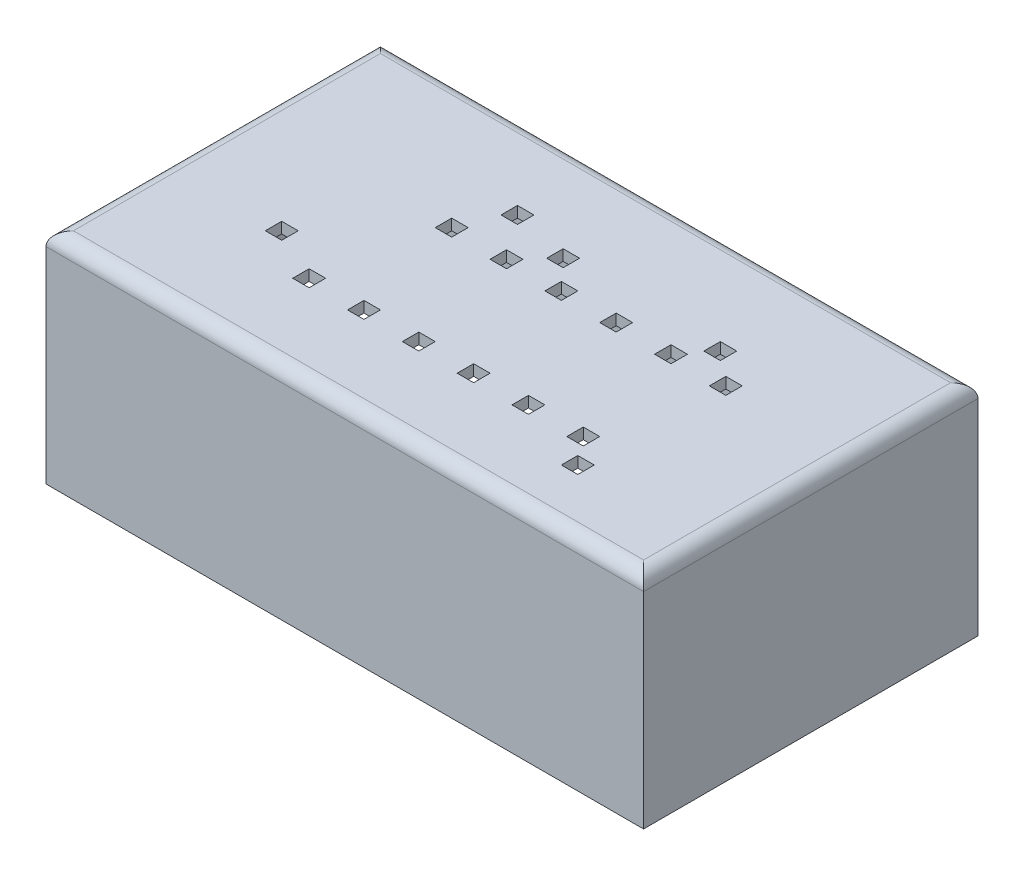
SolidWorks part; units mm, degrees
ref_plane "Front Plane" through (0, 0, 0) normal (0, 0, 1) x (1, 0, 0)
ref_plane "Top Plane" through (0, 0, 0) normal (0, 1, 0) x (1, 0, 0)
ref_plane "Right Plane" through (0, 0, 0) normal (1, 0, 0) x (0, 0, -1)
sketch "Sketch1" plane through (0, 0, 0) normal (0, 1, 0) x (1, 0, 0)
  line L1 (52.5, -28.5) -> (-52.5, -28.5)
  line L2 (52.5, -28.5) -> (52.5, 28.5)
  line L3 (52.5, 28.5) -> (-52.5, 28.5)
  line L4 (-52.5, -28.5) -> (-52.5, 28.5)
  line L5 (52.5, -28.5) -> (-52.5, 28.5) construction
  line L6 (52.5, 28.5) -> (-52.5, -28.5) construction
  point P0 (0, 0)
  dimension "D1" = 57
  dimension "D2" = 105
extrude "Boss-Extrude1" add sketch "Sketch1" against normal blind 2
sketch "Sketch2" plane through (0, 0, 0) normal (0, 1, 0) x (1, 0, 0)
  line L0 (-52.5, 28.5) -> (52.5, 28.5)
  line L1 (52.5, 28.5) -> (52.5, -28.5)
  line L2 (52.5, -28.5) -> (-52.5, -28.5)
  line L3 (-52.5, -28.5) -> (-52.5, 28.5)
  line L4 (-54.5, 30.5) -> (54.5, 30.5)
  line L5 (54.5, 30.5) -> (54.5, -30.5)
  line L6 (54.5, -30.5) -> (-54.5, -30.5)
  line L7 (-54.5, -30.5) -> (-54.5, 30.5)
  dimension "D1" = 2
  dimension "D2" = 2
  dimension "D3" = 2
  dimension "D4" = 2
extrude "Boss-Extrude2" add sketch "Sketch2" against normal blind 40
sketch "Sketch3" plane through (-54.5, 0, 0) normal (-1, 0, 0) x (0, 0, 1)
  line L0 (-21.5, -40) -> (-21.5, -26)
  line L1 (-30.5, -40) -> (30.5, -40) construction
  line L2 (-21.5, -26) -> (-8.5, -26)
  line L3 (-8.5, -26) -> (-8.5, -40)
  line L4 (-8.5, -40) -> (-21.5, -40)
  line L5 (13.5, -40) -> (13.5, -26)
  line L6 (13.5, -26) -> (23.5, -26)
  line L7 (23.5, -26) -> (23.5, -40)
  line L8 (23.5, -40) -> (13.5, -40)
  line L9 (-30.5, -40) -> (-30.5, 0) construction
  line L11 (30.5, -40) -> (30.5, 0) construction
  dimension "D1" = 9
  dimension "D2" = 14
  dimension "D3" = 13
  dimension "D4" = 7
  dimension "D5" = 10
  dimension "D6" = 14
extrude "Cut-Extrude1" cut sketch "Sketch3" against normal up to surface (2 mm away) up to face at (-52.5, -21, 0)
sketch "Sketch4" plane through (0, 0, 0) normal (0, 1, 0) x (1, 0, 0)
  line L0 (-54.5, -15.5) -> (54.5, -15.5) construction
  line L1 (-54.5, 30.5) -> (-54.5, -30.5) construction
  line L2 (54.5, -30.5) -> (54.5, 30.5) construction
  line L3 (-54.5, 5.5) -> (54.5, 5.5) construction
  line L4 (-24.5, 30.5) -> (-24.5, -30.5) construction
  line L5 (54.5, 30.5) -> (-54.5, 30.5) construction
  line L6 (-54.5, -30.5) -> (54.5, -30.5) construction
  line L7 (35.7443, 30.5) -> (35.7443, -30.5) construction
  line L9 (-21.5, -15.5) -> (-24.5, -15.5)
  line L10 (-21.5, -15.5) -> (-21.5, -12.5)
  line L11 (-21.5, -12.5) -> (-24.5, -12.5)
  line L12 (-24.5, -15.5) -> (-24.5, -12.5)
  dimension "D1" = 15
  dimension "D2" = 25
  dimension "D3" = 30
  dimension "D4" = 3
  dimension "D5" = 3
extrude "Cut-Extrude2" cut sketch "Sketch4" against normal up to surface (2 mm away) up to face at (0, -2, 0)
pattern_linear "LPattern1" count 6 spacing 10 along (1, 0, 0) of "Cut-Extrude2"
sketch "Sketch5" plane through (0, 0, 0) normal (0, 1, 0) x (1, 0, 0)
  line L0 (-54.5, 5.5) -> (54.5, 5.5) construction
  line L1 (-54.5, 30.5) -> (-54.5, -30.5) construction
  line L2 (54.5, -30.5) -> (54.5, 30.5) construction
  line L3 (-19.5, 30.5) -> (-19.5, -30.5) construction
  line L4 (54.5, 30.5) -> (-54.5, 30.5) construction
  line L5 (-54.5, -30.5) -> (54.5, -30.5) construction
  line L7 (-19.5, 5.5) -> (-16.5, 5.5)
  line L8 (-19.5, 5.5) -> (-19.5, 8.5)
  line L9 (-19.5, 8.5) -> (-16.5, 8.5)
  line L10 (-16.5, 5.5) -> (-16.5, 8.5)
  dimension "D1" = 35
  dimension "D2" = 25
  dimension "D3" = 3
  dimension "D4" = 3
extrude "Cut-Extrude3" cut sketch "Sketch5" against normal up to surface (2 mm away) up to face at (27, -2, 14)
pattern_linear "LPattern2" count 6 spacing 10 along (1, 0, 0) of "Cut-Extrude3"
sketch "Sketch6" plane through (0, 0, 0) normal (0, 1, 0) x (1, 0, 0)
  line L0 (-19.5, 8.5) -> (-19.5, 5.5) construction
  line L1 (-15.5, 16.5) -> (-12.5, 16.5)
  line L2 (-15.5, 16.5) -> (-15.5, 13.5)
  line L3 (-15.5, 13.5) -> (-12.5, 13.5)
  line L4 (-12.5, 16.5) -> (-12.5, 13.5)
  line L5 (-16.5, 5.5) -> (-19.5, 5.5) construction
  line L6 (-4.5, 13.8318) -> (-1.5, 13.8318)
  line L7 (-4.5, 13.8318) -> (-4.5, 10.8318)
  line L8 (-4.5, 10.8318) -> (-1.5, 10.8318)
  line L9 (-1.5, 13.8318) -> (-1.5, 10.8318)
  point P6 (-18, 5.5)
  dimension "D1" = 3
  dimension "D2" = 3
  dimension "D3" = 4
  dimension "D4" = 8
  dimension "D5" = 3
  dimension "D6" = 3
  dimension "D7" = 8
extrude "Cut-Extrude4" cut sketch "Sketch6" against normal up to surface (2 mm away) up to face at (32, -2, -7)
sketch "Sketch7" plane through (0, 0, 0) normal (0, 1, 0) x (1, 0, 0)
  line L0 (-54.5, 30.5) -> (-54.5, -30.5) construction
  line L1 (-34.5, -7.5) -> (-31.5, -7.5)
  line L2 (-34.5, -7.5) -> (-34.5, -10.5)
  line L3 (-34.5, -10.5) -> (-31.5, -10.5)
  line L4 (-31.5, -7.5) -> (-31.5, -10.5)
  line L5 (-54.5, -30.5) -> (54.5, -30.5) construction
  line L6 (24.5, 13.5) -> (27.5, 13.5)
  line L7 (24.5, 13.5) -> (24.5, 10.5)
  line L8 (24.5, 10.5) -> (27.5, 10.5)
  line L9 (27.5, 13.5) -> (27.5, 10.5)
  line L10 (29.5, -17.5) -> (32.5, -17.5)
  line L11 (29.5, -17.5) -> (29.5, -20.5)
  line L12 (29.5, -20.5) -> (32.5, -20.5)
  line L13 (32.5, -17.5) -> (32.5, -20.5)
  line L14 (23.5, 5.5) -> (23.5, 8.5) construction
  line L15 (28.5, -15.5) -> (28.5, -12.5) construction
  line L16 (25.5, -15.5) -> (28.5, -15.5) construction
  line L17 (23.5, 8.5) -> (20.5, 8.5) construction
  point P16 (23.5, 7)
  dimension "D1" = 3
  dimension "D2" = 20
  dimension "D3" = 20
  dimension "D4" = 3
  dimension "D5" = 3
  dimension "D6" = 1
  dimension "D7" = 1
  dimension "D8" = 2
  dimension "D9" = 2
extrude "Cut-Extrude5" cut sketch "Sketch7" against normal up to surface (2 mm away) up to face at (-3, -2, -12.3318)
fillet "Fillet2" radius 2.5 4 edges at (54.5, 0, 0) (0, 0, 30.5) (-54.5, 0, 0) (0, 0, -30.5)
